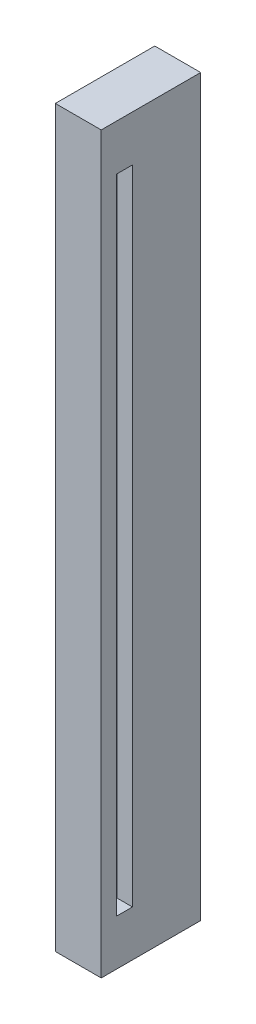
SolidWorks part; units mm, degrees
material "Pine"
ref_plane "Front Plane" through (0, 0, 0) normal (0, 0, 1) x (1, 0, 0)
ref_plane "Top Plane" through (0, 0, 0) normal (0, 1, 0) x (1, 0, 0)
ref_plane "Right Plane" through (0, 0, 0) normal (1, 0, 0) x (0, 0, -1)
sketch "Sketch1" plane through (0, 0, 0) normal (0, 0, 1) x (1, 0, 0)
  line L1 (-9.525, -152.4) -> (9.525, -152.4)
  line L2 (-9.525, -152.4) -> (-9.525, 152.4)
  line L3 (-9.525, 152.4) -> (9.525, 152.4)
  line L4 (9.525, -152.4) -> (9.525, 152.4)
  line L5 (-9.525, -152.4) -> (9.525, 152.4) construction
  line L6 (-9.525, 152.4) -> (9.525, -152.4) construction
  point P0 (0, 0)
  dimension "D1" = 19.05
  dimension "D2" = 304.8
extrude "Boss-Extrude1" add sketch "Sketch1" along normal blind 41.275
sketch "Sketch2" plane through (9.525, 0, 0) normal (1, 0, 0) x (0, 0, -1)
  line L1 (-34.925, 133.35) -> (-28.321, 133.35)
  line L2 (-34.925, 133.35) -> (-34.925, -133.35)
  line L3 (-34.925, -133.35) -> (-28.321, -133.35)
  line L4 (-28.321, 133.35) -> (-28.321, -133.35)
  line L6 (-41.275, -152.4) -> (-41.275, 152.4) construction
  line L8 (-41.275, 152.4) -> (0, 152.4) construction
  point P5 (-28.321, 0)
  dimension "D1" = 19.05
  dimension "D2" = 6.35
  dimension "D3" = 6.604
extrude "Cut-Extrude1" cut sketch "Sketch2" against normal blind 6.35
